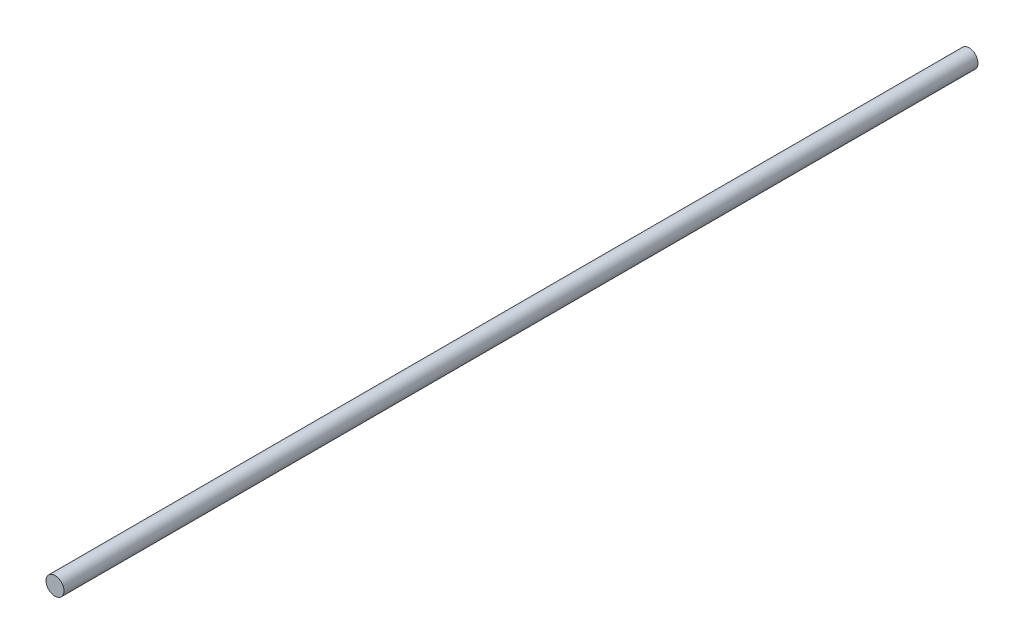
SolidWorks part; units mm, degrees
ref_plane "Front Plane" through (0, 0, 0) normal (0, 0, 1) x (1, 0, 0)
ref_plane "Top Plane" through (0, 0, 0) normal (0, 1, 0) x (1, 0, 0)
ref_plane "Right Plane" through (0, 0, 0) normal (1, 0, 0) x (0, 0, -1)
sketch "Sketch1" plane through (0, 0, 5) normal (0, 0, 1) x (1, 0, 0)
  circle A0 centre (1000, 642) radius 6 construction
  circle A1 centre (1000, 642) radius 6
extrude "Boss-Extrude1" add sketch "Sketch1" against normal up to surface (610 mm away)
